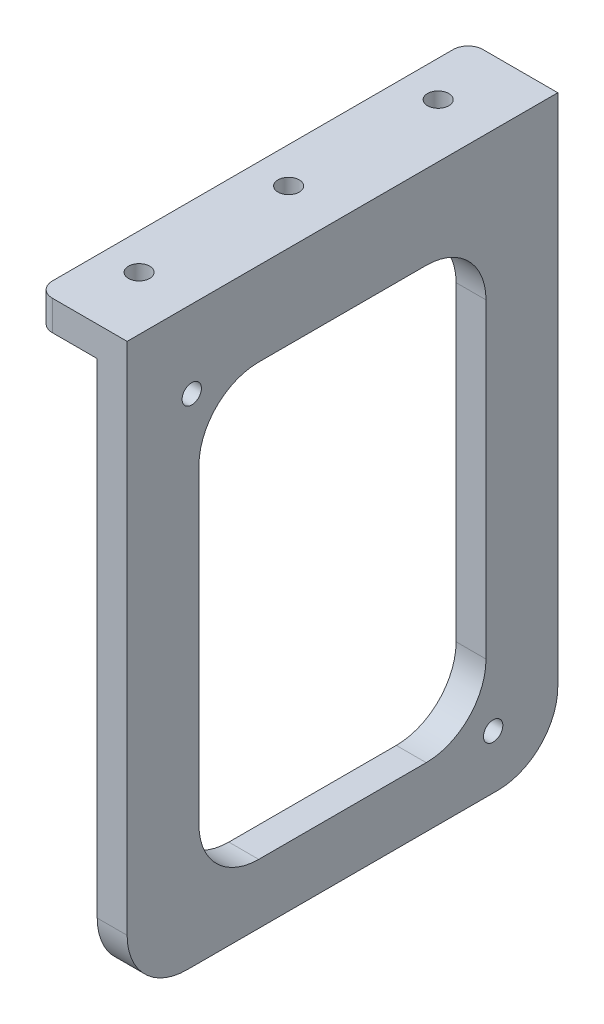
SolidWorks part; units mm, degrees
material "ABS"
ref_plane "Front Plane" through (0, 0, 0) normal (0, 0, 1) x (1, 0, 0)
ref_plane "Top Plane" through (0, 0, 0) normal (0, 1, 0) x (1, 0, 0)
ref_plane "Right Plane" through (0, 0, 0) normal (1, 0, 0) x (0, 0, -1)
sketch "Sketch1" plane through (0, 0, 0) normal (1, 0, 0) x (0, 0, -1)
  line L1 (-22.86, -30.48) -> (22.86, -30.48)
  line L2 (-22.86, -30.48) -> (-22.86, 30.48)
  line L3 (-22.86, 30.48) -> (22.86, 30.48)
  line L4 (22.86, -30.48) -> (22.86, 30.48)
  line L5 (-22.86, -30.48) -> (22.86, 30.48) construction
  line L6 (-22.86, 30.48) -> (22.86, -30.48) construction
  point P0 (0, 0)
  dimension "D1" = 45.72
  dimension "D2" = 60.96
extrude "Boss-Extrude1" add sketch "Sketch1" along normal blind 9.525
sketch "Sketch2" plane through (0, 0, 0) normal (-1, 0, 0) x (0, 0, 1)
  line L0 (22.86, 30.48) -> (22.86, -30.48) construction
  line L1 (-22.86, -30.48) -> (22.86, -30.48)
  line L2 (-22.86, -30.48) -> (-22.86, 27.305)
  line L3 (-22.86, 27.305) -> (22.86, 27.305)
  line L4 (22.86, -30.48) -> (22.86, 27.305)
  line L5 (-22.86, 30.48) -> (22.86, 30.48) construction
  dimension "D1" = 3.175
extrude "Cut-Extrude1" cut sketch "Sketch2" against normal blind 6.35
sketch "Sketch3" plane through (9.525, 0, 0) normal (1, 0, 0) x (0, 0, -1)
  line L2 (-15.24, -24.13) -> (15.24, -24.13)
  line L3 (-15.24, -24.13) -> (-15.24, 21.59)
  line L4 (-15.24, 21.59) -> (15.24, 21.59)
  line L6 (15.24, -24.13) -> (15.24, 21.59)
  line L7 (-15.24, -24.13) -> (15.24, 21.59) construction
  line L8 (-15.24, 21.59) -> (15.24, -24.13) construction
  point P0 (0, -1.27)
  dimension "D1" = 30.48
  dimension "D2" = 45.72
  dimension "D3" = 1.27
extrude "Cut-Extrude2" cut sketch "Sketch3" against normal through all
fillet "Fillet1" radius 6.35 6 edges at (7.9375, -30.48, -22.86) (7.9375, -30.48, 22.86) (7.9375, -24.13, -15.24) (7.9375, -24.13, 15.24) (7.9375, 21.59, -15.24) (7.9375, 21.59, 15.24)
hole_wizard "M2.5x0.45 Tapped Hole1" positions "Sketch5" profile "Sketch4" tap size "M2.5x0.45" standard "Ansi Metric"
sketch "Sketch5" plane through (6.35, 0, 0) normal (-1, 0, 0) x (0, 0, 1)
  line L8 (-16, 22.23) -> (16, 22.23)
  line L9 (-16, 22.23) -> (-16, -24.77)
  line L10 (-16, -24.77) -> (16, -24.77)
  line L11 (16, 22.23) -> (16, -24.77)
  line L12 (-16, 22.23) -> (16, -24.77) construction
  line L13 (-16, -24.77) -> (16, 22.23) construction
  point P0 (16, 22.23)
  point P1 (-16, -24.77)
  point P16 (0, -1.27)
  dimension "D1" = 1.27
  dimension "D3" = 32
  dimension "D4" = 47
sketch "Sketch4" plane through (6.35, 22.23, 16) normal (0, 1, 0) x (0, 0, 1)
  line L0 (0, 0) -> (0, 7.9819)
  line L1 (0, 7.9819) -> (1.025, 7.366)
  line L2 (1.025, 7.366) -> (1.025, 0)
  line L5 (1.025, 0) -> (0, 0)
  line L10 (0, 7.9819) -> (-1.025, 7.366) construction
  line L11 (0, -6.35) -> (0, 107.95) construction
  dimension "Tap Drill Dia." = 2.05
  dimension "Tap Drill Depth" = 7.366
  dimension "Drill Angle" = 118
cosmetic thread "Hole Thread1"
cosmetic thread "Hole Thread2"
hole_wizard "#4-40 Tapped Hole1" positions "Sketch8" profile "Sketch9" tap size "#4-40" standard "Ansi Inch" end condition up to next
sketch "Sketch8" plane through (0, 30.48, 0) normal (0, 1, 0) x (-1, 0, 0)
  line L0 (0, -22.86) -> (0, 22.86) construction
  point P0 (-3.81, -15.875)
  point P1 (-3.81, 15.875)
  point P4 (-3.81, 0)
  dimension "D1" = 15.875
  dimension "D2" = 15.875
  dimension "D3" = 3.81
sketch "Sketch9" plane through (3.81, 30.48, -15.875) normal (1, 0, 0) x (0, 0, 1)
  line L0 (0, 0) -> (0, 3.175)
  line L1 (0, 3.175) -> (1.1303, 3.175)
  line L2 (1.1303, 3.175) -> (1.1303, 0)
  line L5 (1.1303, 0) -> (0, 0)
  line L11 (0, -6.35) -> (0, 107.95) construction
  dimension "Thru Tap Drill Dia." = 2.2606
  dimension "Thru Tap Drill Depth" = 3.175
cosmetic thread "Hole Thread3"
cosmetic thread "Hole Thread4"
cosmetic thread "Hole Thread5"
fillet "Fillet2" radius 1.5875 2 edges at (0, 28.8925, 22.86) (0, 28.8925, -22.86)
